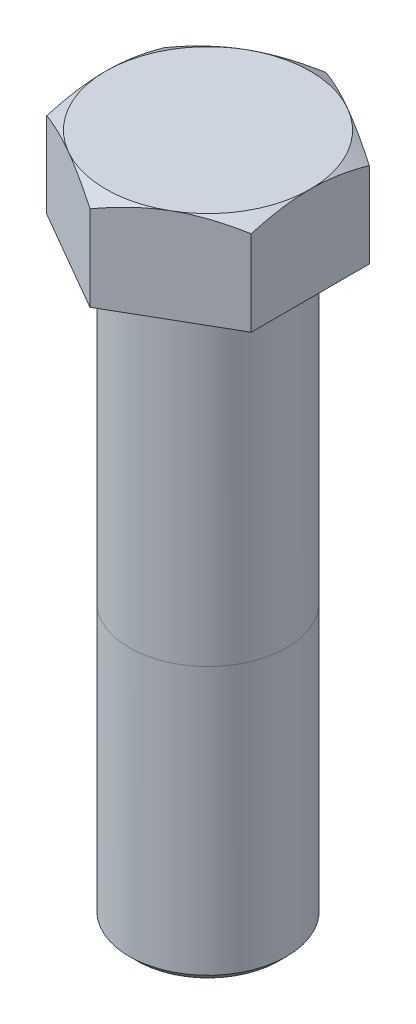
SolidWorks part; units mm, degrees
ref_plane "Front Plane" through (0, 0, 0) normal (0, 0, 1) x (1, 0, 0)
ref_plane "Top Plane" through (0, 0, 0) normal (0, 1, 0) x (1, 0, 0)
ref_plane "Right Plane" through (0, 0, 0) normal (1, 0, 0) x (0, 0, -1)
sketch "Sketch1" plane through (0, 0, 0) normal (0, 1, 0) x (1, 0, 0)
  line L1 (13, 7.5056) -> (0, 15.0111)
  line L2 (0, 15.0111) -> (-13, 7.5056)
  line L3 (-13, 7.5056) -> (-13, -7.5056)
  line L4 (-13, -7.5056) -> (0, -15.0111)
  line L5 (0, -15.0111) -> (13, -7.5056)
  line L6 (13, -7.5056) -> (13, 7.5056)
  circle A0 centre (0, 0) radius 13 construction
  dimension "D1" = 26
extrude "Boss-Extrude1" add sketch "Sketch1" along normal blind 12
sketch "Sketch2" plane through (0, 12, 0) normal (0, 1, 0) x (1, 0, 0)
  line L0 (13, 7.5056) -> (0, 15.0111) construction
  circle A0 centre (0, 0) radius 13
extrude "Cut-Extrude2" cut sketch "Sketch2" against normal blind 12 draft 60 flip side to cut
sketch "Sketch3" plane through (0, 0, 0) normal (0, -1, 0) x (1, 0, 0)
  circle A0 centre (0, 0) radius 10
  dimension "D1" = 20
extrude "Boss-Extrude2" add sketch "Sketch3" along normal blind 75
chamfer "Chamfer1" distance 1 angle 45 1 edges at (0, -75, -10)
sketch "Sketch4" plane through (0, 0, 0) normal (0, 0, 1) x (1, 0, 0)
  line L0 (-10, -40) -> (10, -40)
  line L1 (-10, 0) -> (-10, -74) construction
  line L2 (10, -74) -> (10, 0) construction
  line L3 (-10, 0) -> (10, 0) construction
  dimension "D1" = 40
split line "Split Line1"
